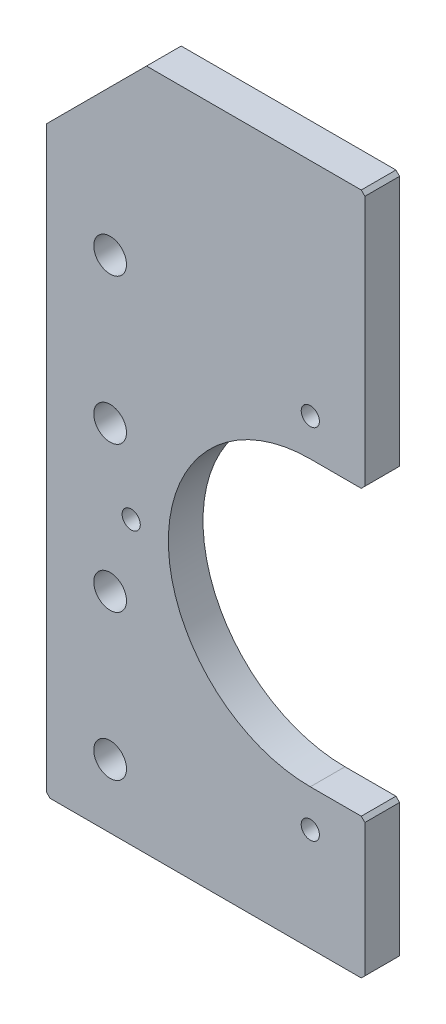
SolidWorks part; units mm, degrees
material "6061-T6 (SS)"
ref_plane "Front Plane" through (0, 0, 0) normal (0, 0, 1) x (1, 0, 0)
ref_plane "Top Plane" through (0, 0, 0) normal (0, 1, 0) x (1, 0, 0)
ref_plane "Right Plane" through (0, 0, 0) normal (1, 0, 0) x (0, 0, -1)
sketch "Sketch1" plane through (0, 0, 0) normal (0, 0, 1) x (1, 0, 0)
  line L0 (0, -39) -> (15, -39)
  line L1 (15, -39) -> (15, -77.5)
  line L2 (15, -77.5) -> (-72.5, -77.5)
  line L3 (-72.5, -77.5) -> (-72.5, 82.5)
  line L4 (-72.5, 82.5) -> (-45, 110)
  line L5 (-45, 110) -> (15, 110)
  line L6 (15, 110) -> (15, 39)
  line L7 (15, 39) -> (0, 39)
  line L8 (-35, 8.8681) -> (-35, 0) construction
  line L9 (-25, 15.1907) -> (-25, 3.6129) construction
  line L10 (-55, 60) -> (-55, 20) construction
  line L11 (-55, 20) -> (-55, -20) construction
  line L12 (-55, -20) -> (-55, -60) construction
  line L13 (5.2388, 0) -> (-5.2388, 0) construction
  arc A0 (0, 39) -> (0, -39) centre (0, 0) ccw
  circle A1 centre (0, 0) radius 49.2125 construction
  point P19 (0, 49.2125)
  point P20 (-49.2125, 0)
  point P21 (0, -49.2125)
  point P22 (-55, 0)
  dimension "D12" = 98.425
  dimension "D1" = 10
  dimension "D2" = 25
  dimension "D3" = 17.5
  dimension "D4" = 40
  dimension "D5" = 20
  dimension "D6" = 17.5
  dimension "D7" = 110
  dimension "D8" = 78
  dimension "D9" = 45
  dimension "D10" = 50
  dimension "D11" = 10
extrude "Boss-Extrude1" add sketch "Sketch1" along normal mid plane 9.525
hole_wizard "M8 Clearance Hole1" positions "Sketch2" profile "Sketch3" hole size "M8" standard "ANSI Metric" end condition up to next
sketch "Sketch2" plane through (0, 0, 4.7625) normal (0, 0, 1) x (1, 0, 0)
  point P0 (-55, 60)
  point P3 (-55, 20)
  point P6 (-55, -20)
  point P9 (-55, -60)
sketch "Sketch3" plane through (-55, 60, 4.7625) normal (1, 0, 0) x (0, -1, 0)
  line L0 (0, 0) -> (0, 9.525)
  line L1 (0, 9.525) -> (4.5, 9.525)
  line L2 (4.5, 9.525) -> (4.5, 0)
  line L5 (4.5, 0) -> (0, 0)
  line L11 (0, -6.35) -> (0, 107.95) construction
  dimension "Thru Hole Dia." = 9
  dimension "Thru Hole Depth" = 9.525
hole_wizard "M6x1.0 Tapped Hole1" positions "Sketch4" profile "Sketch5" tap size "M6x1.0" standard "ANSI Metric" end condition up to next
sketch "Sketch4" plane through (0, 0, 4.7625) normal (0, 0, 1) x (1, 0, 0)
  point P0 (0, 49.2125)
  point P3 (-49.2125, 0)
  point P6 (0, -49.2125)
sketch "Sketch5" plane through (0, 49.2125, 4.7625) normal (1, 0, 0) x (0, -1, 0)
  line L0 (0, 0) -> (0, 9.525)
  line L1 (0, 9.525) -> (2.5, 9.525)
  line L2 (2.5, 9.525) -> (2.5, 0)
  line L5 (2.5, 0) -> (0, 0)
  line L11 (0, -6.35) -> (0, 107.95) construction
  dimension "Thru Tap Drill Dia." = 5
  dimension "Thru Tap Drill Depth" = 9.525
cosmetic thread "Hole Thread1" parameters "D2"=6
cosmetic thread "Hole Thread2" parameters "D2"=6
cosmetic thread "Hole Thread3" parameters "D2"=6
chamfer "Chamfer1" distance 1 5 edges at (-72.5, -77.5, 0) (15, -77.5, 0) (15, -39, 0) (15, 39, 0) (15, 110, 0)
